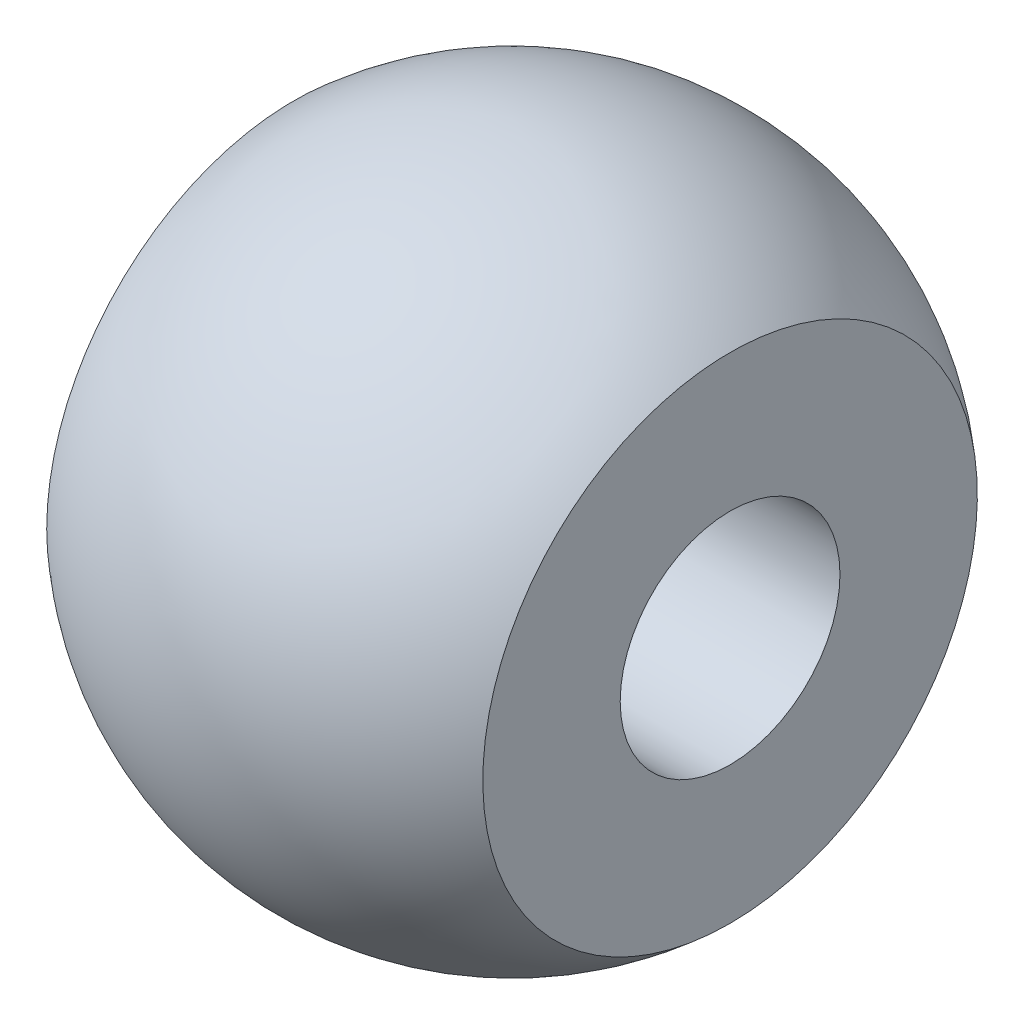
SolidWorks part; units mm, degrees
ref_plane "Front Plane" through (0, 0, 0) normal (0, 0, 1) x (1, 0, 0)
ref_plane "Top Plane" through (0, 0, 0) normal (0, 1, 0) x (1, 0, 0)
ref_plane "Right Plane" through (0, 0, 0) normal (1, 0, 0) x (0, 0, -1)
sketch "Sketch2" plane through (0, 0, 0) normal (0, 0, 1) x (1, 0, 0)
  line L0 (-10.3321, 0) -> (9.6984, 0) construction
  line L1 (-1.4686, -2) -> (3.9686, -2)
  line L2 (-3.9686, 0) -> (-3.9686, -4.5)
  line L3 (-3.9686, -4.5) -> (-1.4686, -2)
  line L4 (3.9686, 0) -> (3.9686, -4.5)
  line L5 (-2.9686, 0) -> (-2.9686, -3.5)
  arc A0 (-3.9686, -4.5) -> (3.9686, -4.5) centre (0, 0) ccw
  dimension "D1" = 4.5
  dimension "D2" = 6
  dimension "D3" = 4.5
  dimension "D4" = 2
  dimension "D5" = 45
  dimension "D6" = 1
revolve "Revolve1" add sketch "Sketch2" angle 360 about L0
